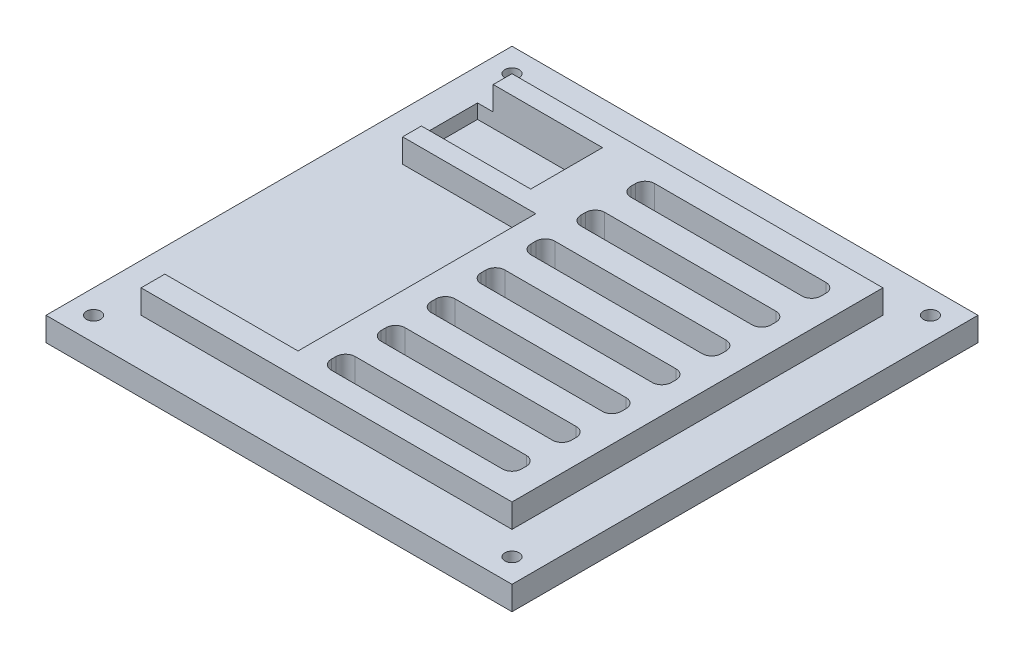
SolidWorks part; units mm, degrees
ref_plane "Front Plane" through (0, 0, 0) normal (0, 0, 1) x (1, 0, 0)
ref_plane "Top Plane" through (0, 0, 0) normal (0, 1, 0) x (1, 0, 0)
ref_plane "Right Plane" through (0, 0, 0) normal (1, 0, 0) x (0, 0, -1)
sketch "Sketch1" plane through (0, 0, 0) normal (0, 1, 0) x (1, 0, 0)
  line L1 (-49, 49) -> (49, 49)
  line L2 (-49, 49) -> (-49, -49)
  line L3 (-49, -49) -> (49, -49)
  line L4 (49, 49) -> (49, -49)
  line L6 (-49, -49) -> (49, 49) construction
  line L9 (0, 0) -> (49, -49) construction
  point P0 (0, 0)
  dimension "D1" = 98
  dimension "D2" = 98
extrude "Boss-Extrude1" add sketch "Sketch1" along normal blind 10
sketch "Sketch4" plane through (0, 10, 0) normal (0, 1, 0) x (1, 0, 0)
  line L1 (44, -44) -> (-44, -44)
  line L2 (44, -44) -> (44, 44)
  line L3 (44, 44) -> (-44, 44)
  line L4 (-44, -44) -> (-44, 44)
  line L7 (-44, 40.4645) -> (-3.5355, 0)
  line L8 (-40.4645, 44) -> (0, 3.5355)
  line L10 (40.4645, 44) -> (0, 3.5355)
  line L11 (44, 40.4645) -> (3.5355, 0)
  line L12 (0, -3.5355) -> (40.4645, -44)
  line L13 (3.5355, 0) -> (44, -40.4645)
  line L14 (0, -3.5355) -> (-40.4645, -44)
  line L15 (-3.5355, 0) -> (-44, -40.4645)
  point P0 (0, 0)
  point P16 (-1.7678, 1.7678)
  dimension "D1" = 88
  dimension "D2" = 88
sketch "Sketch5" plane through (0, 10, 0) normal (0, 1, 0) x (1, 0, 0)
  line L0 (-44, -44) -> (-44, -39) construction
  line L1 (-44, -44) -> (44, -44) construction
  line L2 (-44, -44) -> (-44, 44) construction
  line L3 (-44, 44) -> (44, 44) construction
  line L4 (44, -44) -> (44, 44) construction
  line L5 (-6, 11.5) -> (-6, -39)
  line L6 (-6, -39) -> (-44, -39)
  line L7 (-44, -39) -> (-44, 11.5)
  line L8 (-44, 11.5) -> (-6, 11.5)
  point P0 (0, 0)
sketch "Sketch7" plane through (0, 10, 0) normal (0, 1, 0) x (1, 0, 0)
  line L1 (39, 39) -> (-39, 39)
  line L2 (39, 39) -> (39, -39)
  line L3 (39, -39) -> (-39, -39)
  line L4 (-39, 39) -> (-39, -39)
  line L5 (39, 39) -> (-39, -39) construction
  line L6 (39, -39) -> (-39, 39) construction
  line L7 (49, 49) -> (-49, 49)
  line L8 (49, 49) -> (49, -49)
  line L9 (49, -49) -> (-49, -49)
  line L10 (-49, 49) -> (-49, -49)
  line L11 (49, 49) -> (-49, -49) construction
  line L12 (49, -49) -> (-49, 49) construction
  point P0 (0, 0)
  point P6 (0, 0)
sketch "Sketch8" plane through (0, 10, 0) normal (0, 1, 0) x (1, 0, 0)
  line L1 (49, 49) -> (-49, 49)
  line L2 (49, 49) -> (49, -49)
  line L3 (49, -49) -> (-49, -49)
  line L4 (-49, 49) -> (-49, -49)
  line L5 (39, 39) -> (-39, 39)
  line L6 (39, 39) -> (39, -39)
  line L7 (39, -39) -> (-39, -39)
  line L8 (-39, 39) -> (-39, -39)
  line L9 (39, 39) -> (-39, -39) construction
  line L10 (39, -39) -> (-39, 39) construction
  point P0 (0, 0)
  point P7 (0, 0)
  dimension "D1" = 78
  dimension "D2" = 78
extrude "Cut-Extrude5" cut sketch "Sketch8" against normal blind 5
sketch "Sketch9" plane through (0, 10, 0) normal (0, 1, 0) x (1, 0, 0)
  line L0 (-39, -39) -> (-39, -34)
  line L1 (-39, 39) -> (-39, -39) construction
  line L2 (-39, -34) -> (-49, -34)
  line L3 (-49, 49) -> (-49, -49) construction
  line L5 (-49, -34) -> (-11, -34)
  line L6 (-49, -34) -> (-49, 16)
  line L7 (-49, 16) -> (-11, 16)
  line L8 (-11, -34) -> (-11, 16)
  line M3 (-39, 39) -> (-39, -39)
extrude "Cut-Extrude6" cut sketch "Sketch9" against normal blind 5 contours L5 L8 L7 M3
sketch "Sketch10" plane through (0, 0, 0) normal (0, -1, 0) x (1, 0, 0)
  line L1 (-16.0163, -19.95) -> (-39, -19.95)
  line L2 (-16.0163, -19.95) -> (-16.0163, -35.05)
  line L3 (-16.0163, -35.05) -> (-39, -35.05)
  line L4 (-39, -19.95) -> (-39, -35.05)
sketch "Sketch11" plane through (0, 10, 0) normal (0, 1, 0) x (1, 0, 0)
  line L1 (-39, 35.05) -> (-16.0163, 35.05)
  line L2 (-39, 35.05) -> (-39, 19.95)
  line L3 (-39, 19.95) -> (-16.0163, 19.95)
  line L4 (-16.0163, 35.05) -> (-16.0163, 19.95)
extrude "Cut-Extrude7" cut sketch "Sketch11" against normal blind 8
sketch "Sketch12" plane through (0, 5, 0) normal (0, 1, 0) x (1, 0, 0)
  line L1 (-39, 35.05) -> (-42.3, 35.05)
  line L2 (-39, 35.05) -> (-39, 19.95)
  line L3 (-39, 19.95) -> (-42.3, 19.95)
  line L4 (-42.3, 35.05) -> (-42.3, 19.95)
extrude "Cut-Extrude8" cut sketch "Sketch12" against normal blind 3
sketch "Sketch13" plane through (0, 10, 0) normal (0, 1, 0) x (1, 0, 0)
  line L0 (-4, -18.5) -> (32, -18.5)
  line L1 (-4, -34) -> (32, -34)
  line L3 (-4, -29) -> (32, -29)
  line L5 (34, -21.5) -> (34, -20.5)
  line L6 (-6, -32) -> (-6, -31)
  line L7 (34, -32) -> (34, -31)
  line L8 (-4, -23.5) -> (32, -23.5)
  line L9 (-6, -21.5) -> (-6, -20.5)
  line L10 (-4, -8) -> (32, -8)
  line L11 (34, -11) -> (34, -10)
  line L12 (-4, -13) -> (32, -13)
  line L13 (-6, -11) -> (-6, -10)
  line L14 (-4, 2.5) -> (32, 2.5)
  line L15 (34, -0.5) -> (34, 0.5)
  line L16 (-4, -2.5) -> (32, -2.5)
  line L17 (-6, -0.5) -> (-6, 0.5)
  line L18 (-4, 13) -> (32, 13)
  line L19 (34, 10) -> (34, 11)
  line L20 (-4, 8) -> (32, 8)
  line L21 (-6, 10) -> (-6, 11)
  line L22 (-4, 23.5) -> (32, 23.5)
  line L23 (34, 20.5) -> (34, 21.5)
  line L24 (-4, 18.5) -> (32, 18.5)
  line L25 (-6, 20.5) -> (-6, 21.5)
  line L26 (-4, 34) -> (32, 34)
  line L27 (34, 31) -> (34, 32)
  line L28 (-4, 29) -> (32, 29)
  line L29 (-6, 31) -> (-6, 32)
  arc A0 (34, -31) -> (32, -29) centre (32, -31) ccw
  arc A1 (34, -32) -> (32, -34) centre (32, -32) cw
  arc A2 (-6, -31) -> (-4, -29) centre (-4, -31) cw
  arc A3 (-6, -32) -> (-4, -34) centre (-4, -32) ccw
  arc A4 (-6, -20.5) -> (-4, -18.5) centre (-4, -20.5) cw
  arc A5 (34, -20.5) -> (32, -18.5) centre (32, -20.5) ccw
  arc A6 (34, -21.5) -> (32, -23.5) centre (32, -21.5) cw
  arc A7 (-6, -21.5) -> (-4, -23.5) centre (-4, -21.5) ccw
  arc A8 (-6, -10) -> (-4, -8) centre (-4, -10) cw
  arc A9 (34, -10) -> (32, -8) centre (32, -10) ccw
  arc A10 (34, -11) -> (32, -13) centre (32, -11) cw
  arc A11 (-6, -11) -> (-4, -13) centre (-4, -11) ccw
  arc A12 (-6, 0.5) -> (-4, 2.5) centre (-4, 0.5) cw
  arc A13 (34, 0.5) -> (32, 2.5) centre (32, 0.5) ccw
  arc A14 (34, -0.5) -> (32, -2.5) centre (32, -0.5) cw
  arc A15 (-6, -0.5) -> (-4, -2.5) centre (-4, -0.5) ccw
  arc A16 (-6, 11) -> (-4, 13) centre (-4, 11) cw
  arc A17 (34, 11) -> (32, 13) centre (32, 11) ccw
  arc A18 (34, 10) -> (32, 8) centre (32, 10) cw
  arc A19 (-6, 10) -> (-4, 8) centre (-4, 10) ccw
  arc A20 (-6, 21.5) -> (-4, 23.5) centre (-4, 21.5) cw
  arc A21 (34, 21.5) -> (32, 23.5) centre (32, 21.5) ccw
  arc A22 (34, 20.5) -> (32, 18.5) centre (32, 20.5) cw
  arc A23 (-6, 20.5) -> (-4, 18.5) centre (-4, 20.5) ccw
  arc A24 (-6, 32) -> (-4, 34) centre (-4, 32) cw
  arc A25 (34, 32) -> (32, 34) centre (32, 32) ccw
  arc A26 (34, 31) -> (32, 29) centre (32, 31) cw
  arc A27 (-6, 31) -> (-4, 29) centre (-4, 31) ccw
  dimension "D1" = 2
  dimension "D2" = 7
extrude "Cut-Extrude10" cut sketch "Sketch13" against normal blind 16
sketch "Sketch14" plane through (0, 0, 0) normal (0, -1, 0) x (1, 0, 0)
  line L0 (-44, 0) -> (-35.5474, 0)
  line L1 (44, 44) -> (-44, 44) construction
  line L2 (44, 44) -> (44, -44) construction
  line L3 (44, -44) -> (-44, -44) construction
  line L4 (-44, 44) -> (-44, -44) construction
  line L5 (0, -44) -> (0, -38.0642)
  circle A0 centre (-44, -44) radius 1.5
  circle A1 centre (-44, 44) radius 1.5
  circle A2 centre (44, 44) radius 1.5
  circle A3 centre (44, -44) radius 1.5
  point P0 (0, 0)
  point P14 (0, 0)
  dimension "D1" = 3
extrude "Cut-Extrude11" cut sketch "Sketch14" against normal blind 10 contours A0 | A1 | A2 | A3
